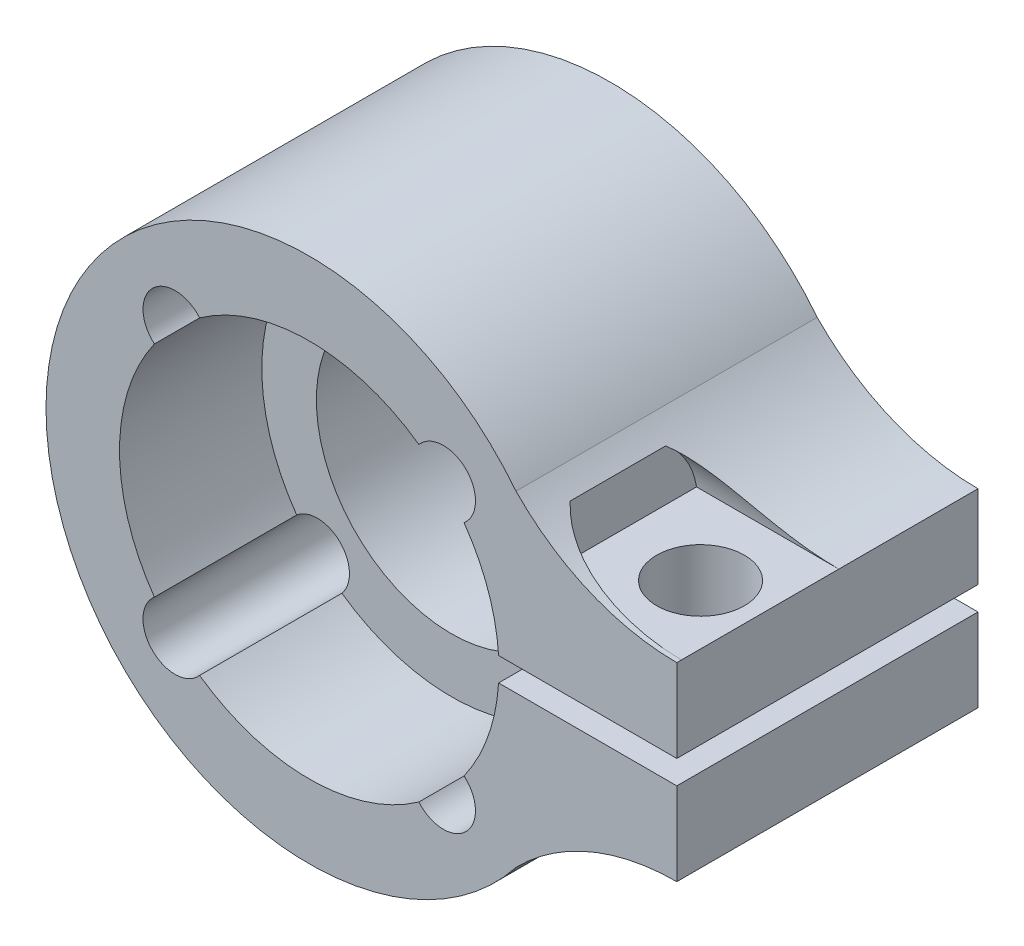
SolidWorks part; units mm, degrees
material "6061 Alloy"
ref_plane "Front Plane" through (0, 0, 0) normal (0, 0, 1) x (1, 0, 0)
ref_plane "Top Plane" through (0, 0, 0) normal (0, 1, 0) x (1, 0, 0)
ref_plane "Right Plane" through (0, 0, 0) normal (1, 0, 0) x (0, 0, -1)
sketch "Sketch1" plane through (0, 0, 0) normal (0, 0, 1) x (1, 0, 0)
  line L0 (-18.136, 0) -> (24.0528, 0) construction
  line L1 (0, 0) -> (0, 0.5)
  line L2 (0, 0.5) -> (15.5, 0.5)
  line L3 (15.5, 0.5) -> (15.5, 4)
  line L5 (0, 0) -> (0, -0.5)
  line L6 (0, -0.5) -> (15.5, -0.5)
  line L7 (15.5, -0.5) -> (15.5, -4)
  arc A0 (8.7199, 6.8683) -> (8.7199, -6.8683) centre (0, 0) ccw
  arc A6 (15.5, 4) -> (8.7199, 6.8683) centre (15.5, 13.4476) cw
  arc A7 (15.5, -4) -> (8.7199, -6.8683) centre (15.5, -13.4476) ccw
  dimension "D1" = 22.2
  dimension "D3" = 0.5
  dimension "D4" = 0.5
  dimension "D5" = 3.5
  dimension "D6" = 3.5
  dimension "D7" = 15.5
  dimension "D8" = 15.5
extrude "Extrude1" add sketch "Sketch1" against normal blind 12.7
sketch "Sketch2" plane through (0, 0, 0) normal (0, 0, 1) x (1, 0, 0)
  circle A1 centre (5.6572, 5.6565) radius 1.85
  circle A2 centre (-5.6572, -5.6565) radius 1.85
  circle A3 centre (5.6565, -5.6572) radius 1.85
  circle A4 centre (-5.6565, 5.6572) radius 1.85
hole_wizard "#6-32 Tapped Hole3" positions "3DSketch3" profile "Sketch5" tap size "#6-32" standard "Ansi Inch" end condition through all
sketch3d "3DSketch3"
  point P0 (-5.6565, 5.6572, 0)
  point P3 (5.6572, 5.6565, 0)
  point P6 (5.6565, -5.6572, 0)
  point P9 (-5.6572, -5.6565, 0)
sketch "Sketch5" plane through (-5.6565, 5.6572, 0) normal (1, 0, 0) x (0, -1, 0)
  line L0 (0, 0) -> (0, 12.7)
  line L1 (0, 12.7) -> (1.3525, 12.7)
  line L2 (1.3525, 12.7) -> (1.3525, 0)
  line L5 (1.3525, 0) -> (0, 0)
  line L11 (0, -6.35) -> (0, 107.95) construction
  dimension "Thru Tap Drill Dia." = 2.7051
  dimension "Thru Tap Drill Depth" = 12.7
cosmetic thread "Hole Thread4" parameters "D2"=3.5052
cosmetic thread "Hole Thread5" parameters "D2"=3.5052
cosmetic thread "Hole Thread6" parameters "D2"=3.5052
cosmetic thread "Hole Thread7" parameters "D2"=3.5052
sketch "Sketch8" plane through (0, 0, 0) normal (0, 0, 1) x (1, 0, 0)
  line L0 (3.9182, -0.5) -> (0, -0.5)
  line L1 (15.5, -0.5) -> (0, -0.5) construction
  line L2 (0, -0.5) -> (0, 0.5)
  line L3 (0, 0.5) -> (3.9182, 0.5)
  line L4 (0, 0.5) -> (15.5, 0.5) construction
  arc A0 (3.9182, 0.5) -> (3.9182, -0.5) centre (0, 0) ccw
  dimension "D1" = 7.9
extrude "Extrude3" [suppressed] add sketch "Sketch8" along normal blind 2.5
sketch "Sketch9" [suppressed] plane through (0, 0, 2.5) normal (0, 0, 1) x (1, 0, 0)
  circle A0 centre (0, 0) radius 2.45
  dimension "D1" = 4.9
extrude "Cut-Extrude3" [suppressed] cut sketch "Sketch9" against normal through all
sketch "Sketch14" plane through (0, 0.5, 0) normal (0, -1, 0) x (1, 0, 0)
  line L0 (15.5, -12.7) -> (15.5, 0) construction
  circle A0 centre (13, -3.5) radius 1.85
  dimension "D1" = 3.7
  dimension "D2" = 2.5
extrude "Cut-Extrude6" cut sketch "Sketch14" against normal through all
hole_wizard "#6-32 Tapped Hole5" positions "Sketch19" profile "Sketch18" tap size "#6-32" standard "Ansi Inch"
sketch "Sketch19" plane through (0, -0.5, 0) normal (0, 1, 0) x (-1, 0, 0)
  line L0 (-15.5, -12.7) -> (-15.5, 0) construction
  point P0 (-13, -3.5)
  dimension "D1" = 2.5
sketch "Sketch18" plane through (13, -0.5, -3.5) normal (1, 0, 0) x (0, 0, 1)
  line L0 (0, 0) -> (0, 51.6127)
  line L1 (0, 51.6127) -> (1.3525, 50.8)
  line L2 (1.3525, 50.8) -> (1.3525, 0)
  line L5 (1.3525, 0) -> (0, 0)
  line L10 (0, 51.6127) -> (-1.3526, 50.8) construction
  line L11 (0, -6.35) -> (0, 107.95) construction
  dimension "Tap Drill Dia." = 2.7051
  dimension "Tap Drill Depth" = 50.8
  dimension "Drill Angle" = 118
cosmetic thread "Hole Thread10" parameters "D1"=4.3212, "D2"=3.5052
sketch "Sketch24" plane through (15.5, 0, 0) normal (1, 0, 0) x (0, 0, -1)
  line L1 (12.7, 4) -> (0, 4) construction
  line L2 (0.2, 4) -> (6.8323, 4)
  arc A0 (0.2, 4) -> (6.8323, 4) centre (3.5162, 3.4607) cw
  dimension "D2" = 0.2
extrude "Cut-Extrude26" cut sketch "Sketch24" against normal blind 6
sketch "Sketch25" plane through (0, 0, 0) normal (0, 0, 1) x (1, 0, 0)
  circle A0 centre (0, 0) radius 5.7
  dimension "D1" = 11.4
extrude "Cut-Extrude27" cut sketch "Sketch25" against normal through all
sketch "Sketch26" plane through (0, 0, 0) normal (0, 0, 1) x (1, 0, 0)
  circle A0 centre (0, 0) radius 8
  dimension "D1" = 16
extrude "Cut-Extrude28" cut sketch "Sketch26" against normal blind 6
